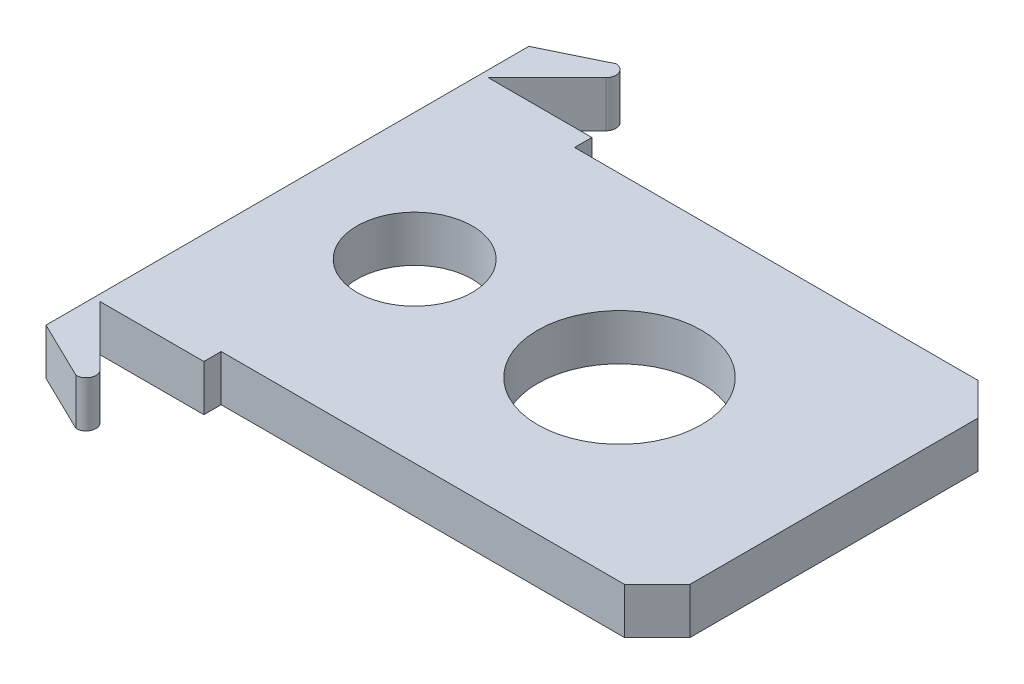
SolidWorks part; units mm, degrees
ref_plane "Front Plane" through (0, 0, 0) normal (0, 0, 1) x (1, 0, 0)
ref_plane "Top Plane" through (0, 0, 0) normal (0, 1, 0) x (1, 0, 0)
ref_plane "Right Plane" through (0, 0, 0) normal (1, 0, 0) x (0, 0, -1)
sketch "Sketch3" plane through (0, 0, 0) normal (0, 1, 0) x (1, 0, 0)
  line L0 (-108.5941, 0) -> (90.7848, 0) construction
  line L1 (40.655, -3.3657) -> (42.455, -3.3657)
  line L2 (42.455, -3.3657) -> (42.455, -3.0657)
  line L3 (42.455, -3.0657) -> (49.455, -3.0657)
  line L4 (49.455, -3.0657) -> (50.0207, -2.5)
  line L5 (50.0207, -2.5) -> (50.0207, 2.5)
  line L6 (40.655, -3.3657) -> (41.6773, -4.388)
  line L7 (41.555, -4.6833) -> (40.5393, -4.1888)
  line L8 (40.5393, -4.1888) -> (40.5393, 4.1888)
  line L9 (41.555, 4.6833) -> (40.5393, 4.1888)
  line L10 (40.655, 3.3657) -> (41.6773, 4.388)
  line L11 (49.455, 3.0657) -> (50.0207, 2.5)
  line L12 (42.455, 3.0657) -> (49.455, 3.0657)
  line L13 (42.455, 3.3657) -> (42.455, 3.0657)
  line L14 (40.655, 3.3657) -> (42.455, 3.3657)
  arc A0 (41.6773, -4.388) -> (41.555, -4.6833) centre (41.555, -4.5103) cw
  arc A1 (41.6773, 4.388) -> (41.555, 4.6833) centre (41.555, 4.5103) ccw
  circle A2 centre (42.7465, 0) radius 1
  circle A3 centre (46.301, 0) radius 1.4214
  point P9 (40.5393, 0)
  point P23 (50.0207, 0)
  dimension "D1" = 7
  dimension "D2" = 0.8
  dimension "D3" = 1.8
  dimension "D4" = 0.3
  dimension "D5" = 2.5
extrude "Boss-Extrude1" add sketch "Sketch3" along normal blind 0.8 contours L0 A2 | A2 L0 | L0 A3 | A3 L0 | L8 L9 A1 L10 L14 L13 L12 L11 L5 L4 L3 L2 L1 L6 A0 L7
